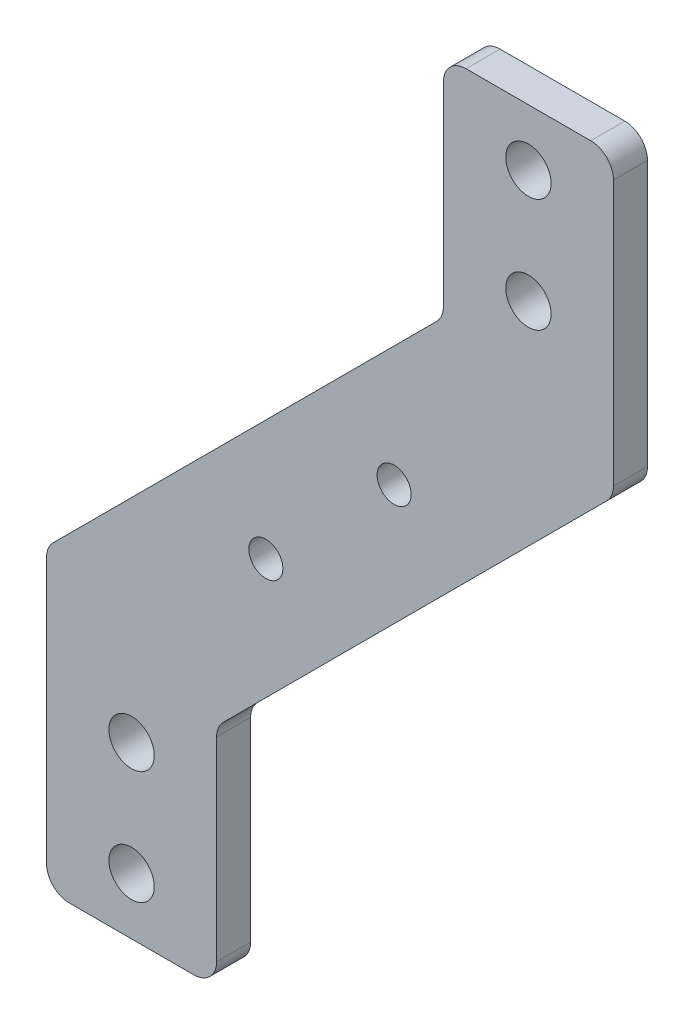
SolidWorks part; units mm, degrees
material "Thornel Mat VMA"
ref_plane "前视基准面" through (0, 0, 0) normal (0, 0, 1) x (1, 0, 0)
ref_plane "上视基准面" through (0, 0, 0) normal (0, 1, 0) x (1, 0, 0)
ref_plane "右视基准面" through (0, 0, 0) normal (1, 0, 0) x (0, 0, -1)
sketch "草图1" plane through (0, 0, 0) normal (0, 0, 1) x (1, 0, 0)
  line L0 (0, 0) -> (-15, 0)
  line L1 (-15, 0) -> (-15, 26.2132)
  line L2 (-15, 26.2132) -> (20, 61.2132)
  line L3 (20, 61.2132) -> (20, 81.2132)
  line L4 (20, 81.2132) -> (35, 81.2132)
  line L5 (35, 81.2132) -> (35, 55)
  line L6 (35, 55) -> (0, 20)
  line L7 (0, 20) -> (0, 0)
  line L8 (-75, 88.5038) -> (-75, -84.3524) construction
  line L9 (-7.5, 15) -> (-7.5, 0) construction
  line L10 (27.5, 81.2132) -> (27.5, 55.9789) construction
  circle A0 centre (-7.5, 15) radius 2
  circle A1 centre (-7.5, 5) radius 2
  circle A2 centre (27.5, 76.2132) radius 2
  circle A3 centre (27.5, 66.2132) radius 2
  dimension "D7" = 4
  dimension "D8" = 4
  dimension "D9" = 10
  dimension "D10" = 5
  dimension "D13" = 4
  dimension "D14" = 4
  dimension "D15" = 10
  dimension "D16" = 5
  dimension "D1" = 220
  dimension "D2" = 150
  dimension "D3" = 45
  dimension "D4" = 15
  dimension "D5" = 15
  dimension "D6" = 15
  dimension "D11" = 20
  dimension "D12" = 20
extrude "凸台-拉伸1" add sketch "草图1" along normal blind 3
fillet "圆角1" radius 2 8 edges at (0, 0, 1.5) (-15, 0, 1.5) (-15, 26.2132, 1.5) (20, 61.2132, 1.5) (20, 81.2132, 1.5) (35, 55, 1.5) (0, 20, 1.5) (35, 81.2132, 1.5)
sketch "草图2" plane through (0, 0, 0) normal (0, 0, -1) x (-1, 0, 0)
  circle A0 centre (-15.6569, 46.2635) radius 1.5
  circle A2 centre (-4.3431, 34.9497) radius 1.5
  dimension "D1" = 3
  dimension "D3" = 3
extrude "切除-拉伸1" cut sketch "草图2" against normal through all
